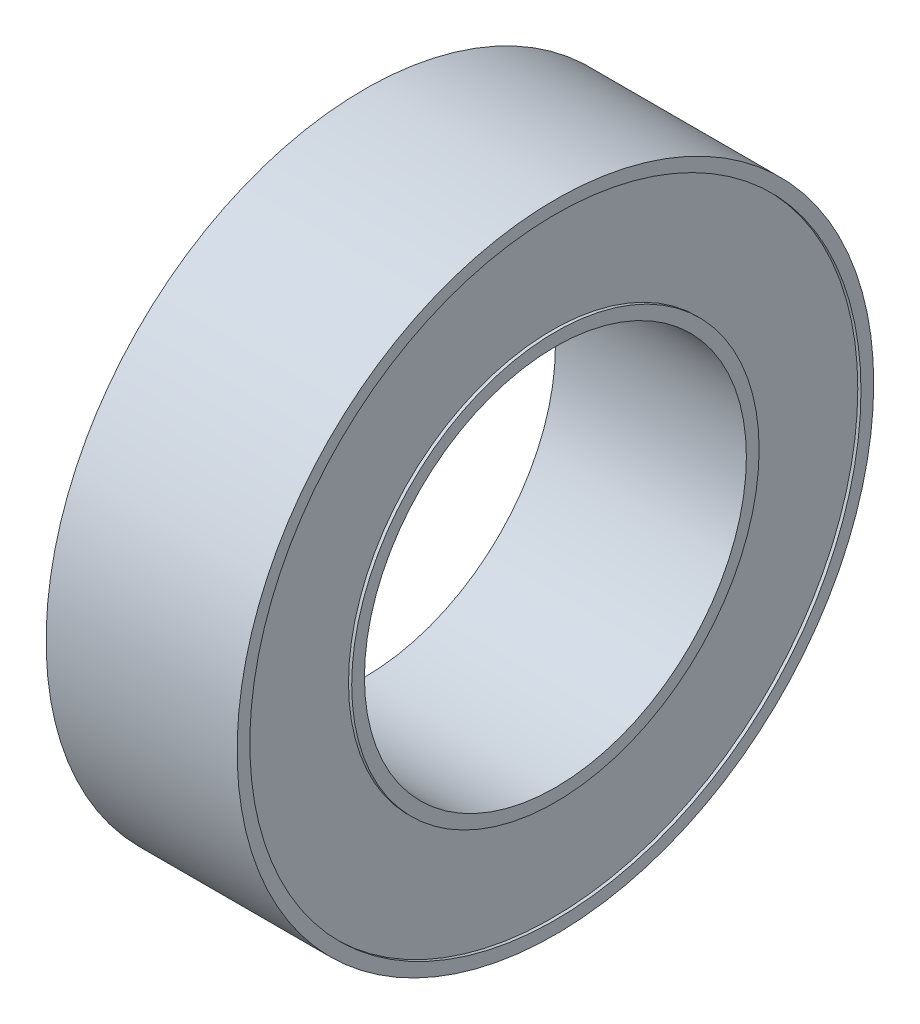
SolidWorks part; units mm, degrees
ref_plane "Front Plane" through (0, 0, 0) normal (0, 0, 1) x (1, 0, 0)
ref_plane "Top Plane" through (0, 0, 0) normal (0, 1, 0) x (1, 0, 0)
ref_plane "Right Plane" through (0, 0, 0) normal (1, 0, 0) x (0, 0, -1)
sketch "Sketch1" plane through (0, 0, 0) normal (1, 0, 0) x (0, 0, -1)
  circle A0 centre (0, 0) radius 5
  circle A1 centre (0, 0) radius 3
  dimension "D1" = 10
  dimension "D2" = 6
extrude "Boss-Extrude1" add sketch "Sketch1" along normal mid plane 3
sketch "Sketch2" plane through (1.5, 0, 0) normal (1, 0, 0) x (0, 0, -1)
  circle A2 centre (0, 0) radius 3.2
  circle A3 centre (0, 0) radius 3.2
  circle A5 centre (0, 0) radius 4.8
  circle A6 centre (0, 0) radius 4.8
  dimension "D1" = 0.2
  dimension "D2" = 0.2
extrude "Cut-Extrude1" cut sketch "Sketch2" against normal blind 0.05
mirror "Mirror1" about plane through (0, 0, 0) normal (1, 0, 0) of "Cut-Extrude1"
